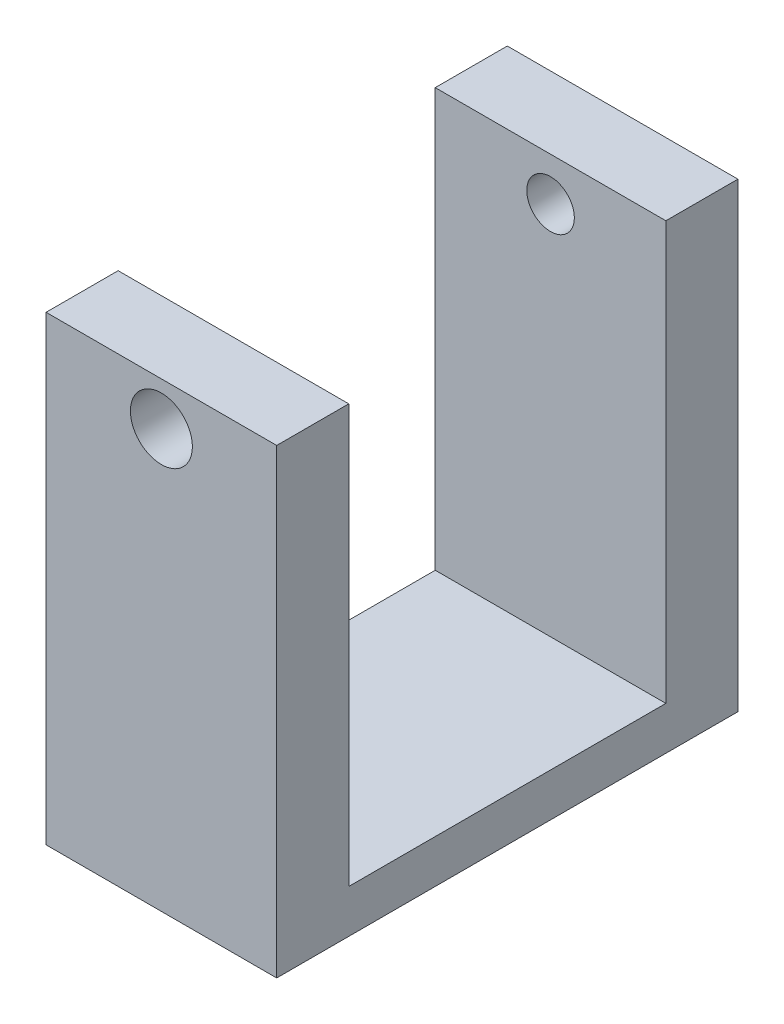
SolidWorks part; units mm, degrees
material "1060 合金"
ref_plane "前视基准面" through (0, 0, 0) normal (0, 0, 1) x (1, 0, 0)
ref_plane "上视基准面" through (0, 0, 0) normal (0, 1, 0) x (1, 0, 0)
ref_plane "右视基准面" through (0, 0, 0) normal (1, 0, 0) x (0, 0, -1)
sketch "草图1" plane through (0, 0, 0) normal (1, 0, 0) x (0, 0, -1)
  line L0 (0, 0) -> (0, 14.818) construction
  line L2 (-11, 32) -> (-11, 3)
  line L3 (-11, 3) -> (11, 3)
  line L4 (11, 32) -> (11, 3)
  line L5 (11, 32) -> (16, 32)
  line L11 (-16, 32) -> (-11, 32)
  line L12 (-16, 32) -> (-16, 0)
  line L13 (-16, 0) -> (16, 0)
  line L14 (16, 32) -> (16, 0)
  dimension "D1" = 22
  dimension "D2" = 5
  dimension "D3" = 29
  dimension "D4" = 3
extrude "凸台-拉伸1" add sketch "草图1" along normal mid plane 16
hole_wizard "M4 间隙孔1" positions "草图3" profile "草图2" hole size "M4" standard "GB"
sketch "草图3" plane through (0, 0, 16) normal (0, 0, 1) x (1, 0, 0)
  line L0 (8, 32) -> (-8, 32) construction
  point P0 (0, 29)
  dimension "D1" = 3
sketch "草图2" plane through (0, 29, 16) normal (1, 0, 0) x (0, -1, 0)
  line L0 (0, 0) -> (0, 5)
  line L1 (0, 5) -> (2.15, 5)
  line L2 (2.15, 5) -> (2.15, 0)
  line L5 (2.15, 0) -> (0, 0)
  line L11 (0, -6.35) -> (0, 107.95) construction
  dimension "通孔孔直径" = 4.3
  dimension "通孔孔深度" = 5
hole_wizard "M4 螺纹孔1" positions "草图5" profile "草图4" tap size "M4" standard "GB" end condition up to next
sketch "草图5" plane through (0, 0, -16) normal (0, 0, -1) x (-1, 0, 0)
  point P0 (0, 29)
sketch "草图4" plane through (0, 29, -16) normal (1, 0, 0) x (0, 1, 0)
  line L0 (0, 0) -> (0, 5)
  line L1 (0, 5) -> (1.65, 5)
  line L2 (1.65, 5) -> (1.65, 0)
  line L5 (1.65, 0) -> (0, 0)
  line L11 (0, -6.35) -> (0, 107.95) construction
  dimension "通孔螺纹孔钻头直径" = 3.3
  dimension "通孔螺纹孔钻头深度" = 5
cosmetic thread "孔螺蚊线1" parameters "D2"=4
hole_wizard "M3 螺纹孔1" positions "草图7" profile "草图6" tap size "M3" standard "GB"
sketch "草图7" plane through (0, 0, 0) normal (0, -1, 0) x (-1, 0, 0)
  line L0 (0, 13.5) -> (0, -13.5) construction
  line L1 (-8, -16) -> (8, -16) construction
  point P0 (0, 13.5)
  point P2 (0, -13.5)
  dimension "D1" = 2.5
cosmetic thread "孔螺蚊线2" parameters "D1"=6, "D2"=3
cosmetic thread "孔螺蚊线3" parameters "D1"=6, "D2"=3
sketch "草图6" plane through (0, 0, -13.5) normal (1, 0, 0) x (0, 0, -1)
  line L0 (0, 0) -> (0, 9.2511)
  line L1 (0, 9.2511) -> (1.25, 8.5)
  line L2 (1.25, 8.5) -> (1.25, 0)
  line L5 (1.25, 0) -> (0, 0)
  line L10 (0, 9.2511) -> (-1.25, 8.5) construction
  line L11 (0, -6.35) -> (0, 107.95) construction
  dimension "螺纹孔钻头直径" = 2.5
  dimension "螺纹孔钻头深度" = 8.5
  dimension "导头角度" = 118
